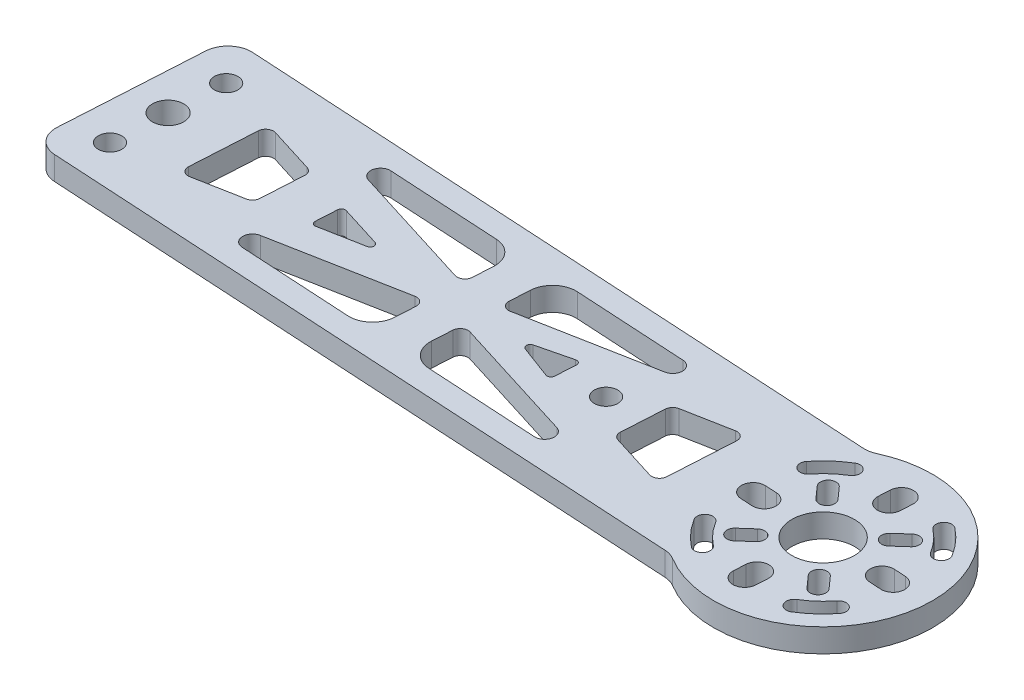
SolidWorks part; units mm, degrees
material "Thornel VCB-20 Carbon Cloth"
ref_plane "Front Plane" through (0, 0, 0) normal (0, 0, 1) x (1, 0, 0)
ref_plane "Top Plane" through (0, 0, 0) normal (0, 1, 0) x (1, 0, 0)
ref_plane "Right Plane" through (0, 0, 0) normal (1, 0, 0) x (0, 0, -1)
sketch "Sketch1" plane through (0, 0, 0) normal (0, 1, 0) x (1, 0, 0)
  line L0 (33.4812, -17.0995) -> (35.0647, 10.288) construction
  line L1 (33.4812, -17.0995) -> (35.0647, 10.288) construction
  line L2 (27.7691, 4.8474) -> (26.9141, -9.1544) construction
  line L3 (23.0653, 10.1138) -> (21.6799, -13.8462)
  line L4 (21.6799, -13.8462) -> (108.3241, -18.8559)
  line L5 (115.5232, -19.2721) -> (116.9086, 4.6879) construction
  line L6 (109.7095, 5.1041) -> (23.0653, 10.1138)
  line L7 (116.2159, -7.2921) -> (22.3726, -1.8662) construction
  line L8 (22.3726, -1.8662) -> (116.2159, -7.2921) construction
  circle A0 centre (26.9141, -9.1544) radius 1.5 construction
  circle A1 centre (27.7691, 4.8474) radius 1.5 construction
  circle A2 centre (26.9141, -9.1544) radius 1.5
  circle A3 centre (27.7691, 4.8474) radius 1.5
  circle A4 centre (116.2159, -7.2921) radius 4
  arc A5 (108.3241, -18.8559) -> (109.7095, 5.1041) centre (116.2159, -7.2921) ccw
  circle A6 centre (27.3416, -2.1535) radius 2
  point P14 (27.3416, -2.1535)
  dimension "D2" = 5
  dimension "D4" = 8
  dimension "D5" = 28
  dimension "D6" = 4
  dimension "D1" = 24
  dimension "D3" = 94
extrude "Boss-Extrude1" add sketch "Sketch1" along normal blind 3 contours L6 L3 L4 A5 | A4 | A3 | A2 | A6
sketch "Sketch2" plane through (0, 0, 0) normal (0, 1, 0) x (1, 0, 0)
  line L0 (35.1692, 2.9031) -> (34.5343, -8.0785)
  line L1 (34.5343, -8.0785) -> (42.6364, -6.5437)
  line L2 (42.6364, -6.5437) -> (43.0405, 0.4447)
  line L3 (109.7095, 5.1041) -> (23.0653, 10.1138)
  line L4 (23.0653, 10.1138) -> (21.6799, -13.8462)
  line L5 (21.6799, -13.8462) -> (108.3241, -18.8559)
  line L6 (109.7095, 5.1041) -> (23.0653, 10.1138) construction
  line L7 (23.0653, 10.1138) -> (21.6799, -13.8462) construction
  line L8 (21.6799, -13.8462) -> (108.3241, -18.8559) construction
  line L9 (43.0405, 0.4447) -> (35.1692, 2.9031)
  line L10 (34.8518, -2.5877) -> (42.8384, -3.0495) construction
  line L11 (27.3416, -2.1535) -> (116.2159, -7.2921) construction
  line L12 (42.6364, -6.5437) -> (56.8151, -3.8576) construction
  line L13 (43.0405, 0.4447) -> (56.8151, -3.8576) construction
  line L14 (48.713, -5.3925) -> (48.9439, -1.3992)
  line L15 (48.9439, -1.3992) -> (56.8151, -3.8576)
  line L16 (48.713, -5.3925) -> (56.8151, -3.8576)
  line L17 (37.8595, 6.2534) -> (64.9243, -2.1998)
  line L18 (64.9243, -2.1998) -> (65.3213, 4.6656)
  line L19 (65.3213, 4.6656) -> (37.8595, 6.2534)
  line L20 (36.8205, -11.7166) -> (64.6792, -6.439)
  line L21 (64.2822, -13.3044) -> (36.8205, -11.7166)
  line L22 (64.6792, -6.439) -> (64.2822, -13.3044)
  line L23 (66.6049, -16.4437) -> (67.9903, 7.5163) construction
  line L24 (69.2739, -13.593) -> (96.7356, -15.1808)
  line L25 (69.6709, -6.7276) -> (69.2739, -13.593)
  line L26 (96.7356, -15.1808) -> (69.6709, -6.7276)
  line L27 (97.7746, 2.7892) -> (69.916, -2.4885)
  line L28 (70.3129, 4.377) -> (97.7746, 2.7892)
  line L29 (69.916, -2.4885) -> (70.3129, 4.377)
  line L30 (81.1588, -7.2685) -> (74.7851, -4.8966)
  line L31 (81.1588, -7.2685) -> (81.3897, -3.2752)
  line L32 (81.3897, -3.2752) -> (74.7851, -4.8966)
  line L33 (100.0609, -0.8489) -> (99.4259, -11.8305)
  line L34 (91.9588, -2.3838) -> (100.0609, -0.8489)
  line L35 (91.5547, -9.3721) -> (91.9588, -2.3838)
  line L36 (99.4259, -11.8305) -> (91.5547, -9.3721)
  line L37 (116.2159, -7.2921) -> (127.1975, -7.9271) construction
  line L38 (116.2159, -7.2921) -> (116.8508, 3.6895) construction
  line L39 (116.2159, -7.2921) -> (115.5809, -18.2738) construction
  line L40 (108.8997, 0.9221) -> (123.5321, -15.5063) construction
  line L41 (108.0017, -14.6084) -> (124.4301, 0.0241) construction
  line L42 (120.2066, -11.7726) -> (121.5368, -13.2661) construction
  line L43 (120.9533, -11.1075) -> (122.2835, -12.601)
  line L44 (119.4598, -12.4377) -> (120.79, -13.9312)
  line L45 (115.6675, -16.7763) -> (115.7541, -15.2788) construction
  line L46 (114.17, -16.6897) -> (114.2566, -15.1922)
  line L47 (117.165, -16.8629) -> (117.2516, -15.3654)
  line L48 (120.6963, -3.3015) -> (122.1898, -1.9712) construction
  line L49 (121.3615, -4.0482) -> (122.8549, -2.718)
  line L50 (120.0312, -2.5547) -> (121.5247, -1.2245)
  line L51 (116.7643, 2.192) -> (116.6777, 0.6945) construction
  line L52 (115.2668, 2.2786) -> (115.1802, 0.7811)
  line L53 (118.2617, 2.1054) -> (118.1752, 0.6079)
  line L54 (112.2252, -2.8117) -> (110.895, -1.3182) construction
  line L55 (112.972, -2.1466) -> (111.6417, -0.6531)
  line L56 (111.4785, -3.4768) -> (110.1482, -1.9833)
  line L57 (111.7354, -11.2828) -> (110.2419, -12.613) construction
  line L58 (112.4005, -12.0295) -> (110.907, -13.3598)
  line L59 (111.0703, -10.5361) -> (109.5768, -11.8663)
  line L60 (125.7, -7.8405) -> (124.2025, -7.7539) construction
  line L61 (125.7866, -6.343) -> (124.2891, -6.2564)
  line L62 (125.6135, -9.338) -> (124.116, -9.2514)
  line L63 (106.7317, -6.7438) -> (108.2292, -6.8304) construction
  line L64 (106.8183, -5.2463) -> (108.3158, -5.3329)
  line L65 (106.6451, -8.2413) -> (108.1426, -8.3278)
  circle A0 centre (116.2159, -7.2921) radius 4 construction
  arc A1 (108.3241, -18.8559) -> (109.7095, 5.1041) centre (116.2159, -7.2921) ccw
  arc A2 (108.3241, -18.8559) -> (109.7095, 5.1041) centre (116.2159, -7.2921) ccw construction
  circle A3 centre (26.9141, -9.1544) radius 1.5 construction
  circle A4 centre (27.3416, -2.1535) radius 2 construction
  circle A5 centre (27.7691, 4.8474) radius 1.5 construction
  circle A6 centre (116.2159, -7.2921) radius 4 construction
  circle A7 centre (26.9141, -9.1544) radius 1.5 construction
  circle A8 centre (27.3416, -2.1535) radius 2 construction
  circle A9 centre (27.7691, 4.8474) radius 1.5 construction
  circle A10 centre (86.7651, -5.5893) radius 1.5
  circle A11 centre (116.2159, -7.2921) radius 11 construction
  arc A12 (121.9167, -16.6996) -> (124.9037, -14.0392) centre (116.2159, -7.2921) ccw construction
  arc A13 (122.4349, -17.5549) -> (125.6934, -14.6526) centre (116.2159, -7.2921) ccw
  arc A14 (121.3984, -15.8444) -> (124.1139, -13.4258) centre (116.2159, -7.2921) ccw
  arc A15 (121.3984, -15.8444) -> (122.4349, -17.5549) centre (121.9167, -16.6996) ccw
  arc A16 (125.6934, -14.6526) -> (124.1139, -13.4258) centre (124.9037, -14.0392) ccw
  arc A17 (120.9533, -11.1075) -> (119.4598, -12.4377) centre (120.2066, -11.7726) ccw
  arc A18 (120.79, -13.9312) -> (122.2835, -12.601) centre (121.5368, -13.2661) ccw
  arc A19 (114.17, -16.6897) -> (117.165, -16.8629) centre (115.6675, -16.7763) ccw
  arc A20 (117.2516, -15.3654) -> (114.2566, -15.1922) centre (115.7541, -15.2788) ccw
  arc A21 (121.3615, -4.0482) -> (120.0312, -2.5547) centre (120.6963, -3.3015) cw
  arc A22 (121.5247, -1.2245) -> (122.8549, -2.718) centre (122.1898, -1.9712) cw
  arc A23 (122.9629, 1.3956) -> (125.6234, -1.5913) centre (116.2159, -7.2921) cw construction
  arc A24 (123.5763, 2.1854) -> (126.4786, -1.0731) centre (116.2159, -7.2921) cw
  arc A25 (122.3496, 0.6058) -> (124.7682, -2.1096) centre (116.2159, -7.2921) cw
  arc A26 (122.3496, 0.6058) -> (123.5763, 2.1854) centre (122.9629, 1.3956) cw
  arc A27 (126.4786, -1.0731) -> (124.7682, -2.1096) centre (125.6234, -1.5913) cw
  arc A28 (115.2668, 2.2786) -> (118.2617, 2.1054) centre (116.7643, 2.192) cw
  arc A29 (118.1752, 0.6079) -> (115.1802, 0.7811) centre (116.6777, 0.6945) cw
  arc A30 (112.972, -2.1466) -> (111.4785, -3.4768) centre (112.2252, -2.8117) cw
  arc A31 (110.1482, -1.9833) -> (111.6417, -0.6531) centre (110.895, -1.3182) cw
  arc A32 (107.5281, -0.5451) -> (110.5151, 2.1154) centre (116.2159, -7.2921) cw construction
  arc A33 (106.7383, 0.0683) -> (109.9968, 2.9706) centre (116.2159, -7.2921) cw
  arc A34 (108.3179, -1.1585) -> (111.0333, 1.2601) centre (116.2159, -7.2921) cw
  arc A35 (108.3179, -1.1585) -> (106.7383, 0.0683) centre (107.5281, -0.5451) cw
  arc A36 (109.9968, 2.9706) -> (111.0333, 1.2601) centre (110.5151, 2.1154) cw
  arc A37 (106.8084, -12.9929) -> (109.4688, -15.9799) centre (116.2159, -7.2921) ccw construction
  arc A38 (105.9532, -13.5112) -> (108.8555, -16.7697) centre (116.2159, -7.2921) ccw
  arc A39 (107.6636, -12.4747) -> (110.0822, -15.1901) centre (116.2159, -7.2921) ccw
  arc A40 (107.6636, -12.4747) -> (105.9532, -13.5112) centre (106.8084, -12.9929) ccw
  arc A41 (108.8555, -16.7697) -> (110.0822, -15.1901) centre (109.4688, -15.9799) ccw
  arc A42 (112.4005, -12.0295) -> (111.0703, -10.5361) centre (111.7354, -11.2828) ccw
  arc A43 (109.5768, -11.8663) -> (110.907, -13.3598) centre (110.2419, -12.613) ccw
  arc A44 (125.7866, -6.343) -> (125.6135, -9.338) centre (125.7, -7.8405) cw
  arc A45 (124.116, -9.2514) -> (124.2891, -6.2564) centre (124.2025, -7.7539) cw
  arc A46 (106.8183, -5.2463) -> (106.6451, -8.2413) centre (106.7317, -6.7438) ccw
  arc A47 (108.1426, -8.3278) -> (108.3158, -5.3329) centre (108.2292, -6.8304) ccw
  point P42 (22.3726, -1.8662)
  point P47 (81.2742, -5.2718)
  point P61 (123.5321, -15.5063)
  point P66 (120.8717, -12.5193)
  point P67 (122.867, -14.7596)
  point P68 (124.1972, -16.2531)
  point P75 (122.2019, -14.0128)
  point P76 (119.5414, -11.0259)
  point P79 (115.7108, -16.0275)
  point P84 (114.2133, -15.941)
  point P90 (121.4431, -2.6364)
  point P97 (124.4301, 0.0241)
  point P104 (116.721, 1.4433)
  point P111 (111.5601, -2.0649)
  point P118 (108.8997, 0.9221)
  point P125 (108.0017, -14.6084)
  point P132 (110.9887, -11.9479)
  point P139 (124.9513, -7.7972)
  point P146 (107.4805, -6.7871)
  dimension "D11" = 3
  dimension "D16" = 22
  dimension "D22" = 5
  dimension "D2" = 12.5
  dimension "D3" = 8
  dimension "D4" = 11
  dimension "D5" = 7
  dimension "D6" = 6
  dimension "D7" = 4
  dimension "D8" = 3
  dimension "D9" = 42.5
  dimension "D10" = 45
  dimension "D12" = 64.5
  dimension "D13" = 18
  dimension "D14" = 5.5
  dimension "D15" = 4
  dimension "D17" = 45
  dimension "D18" = 45
  dimension "D19" = 2
  dimension "D20" = 4
  dimension "D21" = 1
  dimension "D23" = 2
  dimension "D24" = 3
  dimension "D25" = 8
  dimension "D26" = 9.5
  dimension "D1" = 0
extrude "Cut-Extrude2" cut sketch "Sketch2" along normal blind 3
fillet "Fillet1" radius 1 8 edges at (42.6364, 1.5, 6.5437) (34.5343, 1.5, 8.0785) (35.1692, 1.5, -2.9031) (43.0405, 1.5, -0.4447) (99.4259, 1.5, 11.8305) (91.5547, 1.5, 9.3721) (91.9588, 1.5, 2.3838) (100.0609, 1.5, 0.8489)
fillet "Fillet2" radius 1.25 4 edges at (36.8205, 1.5, 11.7166) (37.8595, 1.5, -6.2534) (96.7356, 1.5, 15.1808) (97.7746, 1.5, -2.7892)
fillet "Fillet3" radius 3 4 edges at (65.3213, 1.5, -4.6656) (64.2822, 1.5, 13.3044) (69.2739, 1.5, 13.593) (70.3129, 1.5, -4.377)
fillet "Fillet4" radius 1 4 edges at (64.6792, 1.5, 6.439) (64.9243, 1.5, 2.1998) (69.6709, 1.5, 6.7276) (69.916, 1.5, 2.4885)
fillet "Fillet5" radius 0.5 6 edges at (56.8151, 1.5, 3.8576) (48.9439, 1.5, 1.3992) (48.713, 1.5, 5.3925) (81.3897, 1.5, 3.2752) (81.1588, 1.5, 7.2685) (74.7851, 1.5, 4.8966)
fillet "Fillet6" radius 3 4 edges at (109.7095, 1.5, -5.1041) (108.3241, 1.5, 18.8559) (23.0653, 1.5, -10.1138) (21.6799, 1.5, 13.8462)
